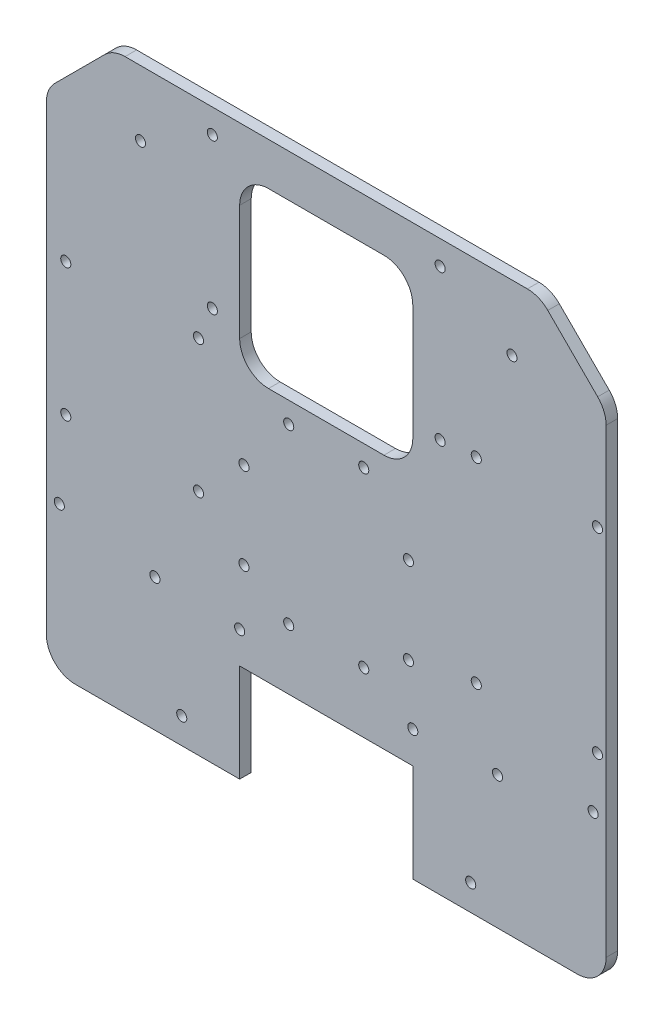
SolidWorks part; units mm, degrees
material "PMMA"
ref_plane "前视基准面" through (0, 0, 0) normal (0, 0, 1) x (1, 0, 0)
ref_plane "上视基准面" through (0, 0, 0) normal (0, 1, 0) x (1, 0, 0)
ref_plane "右视基准面" through (0, 0, 0) normal (1, 0, 0) x (0, 0, -1)
sketch "草图3" plane through (0, 0, 0) normal (0, 0, 1) x (1, 0, 0)
  line L1 (73.5057, 259.0895) -> (196.9372, 259.0895)
  line L2 (25.2215, 210.8052) -> (25.2215, 54.0895)
  line L3 (45.2215, 34.0895) -> (225.2215, 34.0895)
  line L4 (245.2215, 210.8052) -> (245.2215, 54.0895)
  line L6 (31.0793, 224.9474) -> (59.3636, 253.2316)
  line L9 (211.0793, 253.2316) -> (239.3636, 224.9474)
  arc A0 (73.5057, 259.0895) -> (59.3636, 253.2316) centre (73.5057, 239.0895) ccw
  arc A1 (211.0793, 253.2316) -> (196.9372, 259.0895) centre (196.9372, 239.0895) ccw
  arc A2 (31.0793, 224.9474) -> (25.2215, 210.8052) centre (45.2215, 210.8052) ccw
  arc A3 (25.2215, 54.0895) -> (45.2215, 34.0895) centre (45.2215, 54.0895) ccw
  arc A4 (225.2215, 34.0895) -> (245.2215, 54.0895) centre (225.2215, 54.0895) ccw
  arc A5 (245.2215, 210.8052) -> (239.3636, 224.9474) centre (225.2215, 210.8052) ccw
  dimension "D1" = 20
  dimension "D2" = 20
  dimension "D3" = 20
extrude "凸台-拉伸1" add sketch "草图3" along normal blind 4
ref_plane "基准面1" through (0, 0, 4) normal (0, 0, 1) x (1, 0, 0)
sketch "草图4" plane through (0, 0, 4) normal (0, 0, 1) x (1, 0, 0)
  line L0 (135.2215, 259.0895) -> (135.2215, 34.0895) construction
  line L1 (135.2215, 232.7454) -> (174.6915, 232.7454) construction
  line L2 (154.9565, 232.7454) -> (154.9565, 180.6354) construction
  line L4 (135.2215, 180.6354) -> (154.9565, 180.6354) construction
  line L6 (154.9565, 206.6904) -> (187.4334, 206.6904) construction
  line L10 (196.9372, 259.0895) -> (73.5057, 259.0895) construction
  line L11 (45.2215, 34.0895) -> (225.2215, 34.0895) construction
  line L13 (135.2215, 89.0683) -> (165.2215, 89.0683) construction
  circle A5 centre (174.6915, 232.7454) radius 1.75
  circle A14 centre (174.6915, 180.6354) radius 1.75
  circle A15 centre (95.7515, 180.6354) radius 1.75
  circle A16 centre (95.7515, 232.7454) radius 1.75
  circle A17 centre (165.2215, 89.0683) radius 1.75
  circle A18 centre (105.2215, 89.0683) radius 1.75
sketch "草图6" plane through (0, 0, 4) normal (0, 0, 1) x (1, 0, 0)
  line L0 (135.2215, 265.6507) -> (135.2215, 27.2875) construction
  line L1 (187.2215, 181.7201) -> (187.2215, 113.8801) construction
  line L4 (229.2215, 181.7201) -> (229.2215, 113.8801) construction
  line L6 (187.2215, 181.7201) -> (229.2215, 181.7201) construction
  line L7 (187.2215, 113.8801) -> (229.2215, 113.8801) construction
  circle A0 centre (187.2215, 181.7201) radius 1.75
  circle A1 centre (229.2215, 181.7201) radius 1.75
  circle A2 centre (229.2215, 113.8801) radius 1.75
  circle A3 centre (187.2215, 113.8801) radius 1.75
extrude "切除-拉伸3" cut sketch "草图6" against normal blind 4
extrude "切除-拉伸4" cut sketch "草图4" against normal blind 4
sketch "草图7" plane through (0, 0, 4) normal (0, 0, 1) x (1, 0, 0)
  circle A0 centre (122.2215, 159.0895) radius 1.75
  circle A1 centre (148.2215, 159.0895) radius 1.75
  circle A2 centre (122.2215, 99.0895) radius 1.75
  circle A3 centre (148.2215, 99.0895) radius 1.75
extrude "切除-拉伸5" cut sketch "草图7" against normal blind 4
sketch "草图8" plane through (0, 0, 4) normal (0, 0, 1) x (1, 0, 0)
  line L0 (25.2215, 132.4474) -> (245.2215, 132.4474) construction
  line L1 (105.2215, 89.0683) -> (165.2215, 89.0683) construction
  line L2 (227.7201, 95.4947) -> (185.2937, 53.0683) construction
  line L4 (25.2215, 210.8052) -> (25.2215, 54.0895) construction
  line L5 (245.2215, 210.8052) -> (245.2215, 54.0895) construction
  line L7 (135.2215, 259.0895) -> (135.2215, 34.0895) construction
  circle A2 centre (227.7201, 95.4947) radius 1.75
  circle A3 centre (185.2937, 53.0683) radius 1.75
  circle A4 centre (42.7229, 95.4947) radius 1.75
  circle A5 centre (85.1493, 53.0683) radius 1.75
extrude "切除-拉伸6" cut sketch "草图8" against normal blind 4
sketch "草图9" plane through (0, 0, 4) normal (0, 0, 1) x (1, 0, 0)
  line L0 (115.2215, 166.3247) -> (155.2215, 166.3247)
  line L2 (135.2215, 226.3247) -> (115.2215, 226.3247)
  line L6 (155.2215, 226.3247) -> (135.2215, 226.3247)
  line L9 (105.2215, 196.1043) -> (105.2215, 176.3247)
  line L10 (105.2215, 166.3247) -> (115.2215, 166.3247)
  line L11 (115.2215, 226.3247) -> (105.2215, 226.3247)
  line L12 (105.2215, 216.3247) -> (105.2215, 196.1043)
  line L13 (155.2215, 226.3247) -> (165.2215, 226.3247)
  line L14 (165.2215, 216.3247) -> (165.2215, 176.3247)
  line L15 (165.2215, 166.3247) -> (155.2215, 166.3247)
  arc A0 (165.2215, 216.3247) -> (155.2215, 226.3247) centre (155.2215, 216.3247) ccw
  arc A1 (165.2215, 176.3247) -> (155.2215, 166.3247) centre (155.2215, 176.3247) cw
  arc A2 (115.2215, 166.3247) -> (105.2215, 176.3247) centre (115.2215, 176.3247) cw
  arc A3 (105.2215, 216.3247) -> (115.2215, 226.3247) centre (115.2215, 216.3247) cw
  dimension "D1" = 10
extrude "切除-拉伸7" cut sketch "草图9" against normal blind 4
sketch "草图10" plane through (0, 0, 4) normal (0, 0, 1) x (1, 0, 0)
  line L0 (135.2215, 259.0895) -> (135.2215, 34.0895) construction
  line L1 (196.9372, 259.0895) -> (73.5057, 259.0895) construction
  line L2 (45.2215, 34.0895) -> (225.2215, 34.0895) construction
  line L3 (106.7215, 109.0895) -> (106.7215, 139.0895) construction
  line L4 (106.7215, 139.0895) -> (163.7215, 139.0895) construction
  line L5 (163.7215, 139.0895) -> (163.7215, 109.0895) construction
  line L6 (163.7215, 109.0895) -> (106.7215, 109.0895) construction
  line L7 (45.2215, 34.0895) -> (225.2215, 34.0895) construction
  circle A2 centre (106.7215, 109.0895) radius 1.75
  circle A3 centre (163.7215, 109.0895) radius 1.75
  circle A4 centre (106.7215, 139.0895) radius 1.75
  circle A5 centre (163.7215, 139.0895) radius 1.75
  dimension "D1" = 75
extrude "切除-拉伸9" cut sketch "草图10" against normal blind 4
sketch "草图11" plane through (0, 0, 4) normal (0, 0, 1) x (1, 0, 0)
  line L0 (26.7439, 218.4589) -> (243.6991, 218.4589) construction
  line L1 (65.8521, 257.5671) -> (65.8521, 34.0895) construction
  line L2 (45.2215, 34.0895) -> (225.2215, 34.0895) construction
  line L3 (204.5909, 131.2717) -> (65.8521, 131.2717) construction
  line L4 (25.2215, 54.0895) -> (245.2215, 54.0895) construction
  line L5 (135.2215, 259.0895) -> (135.2215, 34.0895) construction
  line L10 (73.254, 90.0846) -> (74.553, 87.8346)
  line L11 (73.4502, 218.4589) -> (72.1511, 220.7089)
  line L12 (196.9372, 259.0895) -> (73.5057, 259.0895) construction
  line L13 (204.5909, 218.4589) -> (204.5909, 44.0846) construction
  line L26 (75.8521, 90.0846) -> (75.8521, 218.4589) construction
  line L27 (72.1511, 220.7089) -> (69.553, 220.7089)
  line L28 (69.553, 220.7089) -> (68.254, 218.4589)
  line L29 (68.254, 218.4589) -> (69.553, 216.2089)
  line L30 (69.553, 216.2089) -> (72.1511, 216.2089)
  line L31 (72.1511, 216.2089) -> (73.4502, 218.4589)
  line L32 (77.1511, 87.8346) -> (78.4502, 90.0846)
  line L33 (74.553, 87.8346) -> (77.1511, 87.8346)
  line L34 (78.4502, 90.0846) -> (77.1511, 92.3346)
  line L35 (74.553, 92.3346) -> (73.254, 90.0846)
  line L36 (77.1511, 92.3346) -> (74.553, 92.3346)
  line L37 (191.9928, 90.0846) -> (193.2918, 87.8346)
  line L38 (195.8899, 87.8346) -> (197.1889, 90.0846)
  line L39 (193.2918, 87.8346) -> (195.8899, 87.8346)
  line L40 (197.1889, 90.0846) -> (195.8899, 92.3346)
  line L41 (193.2918, 92.3346) -> (191.9928, 90.0846)
  line L42 (195.8899, 92.3346) -> (193.2918, 92.3346)
  line L43 (196.9928, 218.4589) -> (198.2918, 216.2089)
  line L44 (200.8899, 216.2089) -> (202.1889, 218.4589)
  line L45 (198.2918, 216.2089) -> (200.8899, 216.2089)
  line L46 (202.1889, 218.4589) -> (200.8899, 220.7089)
  line L47 (198.2918, 220.7089) -> (196.9928, 218.4589)
  line L48 (200.8899, 220.7089) -> (198.2918, 220.7089)
  arc A0 (31.0793, 224.9474) -> (25.2215, 210.8052) centre (45.2215, 210.8052) ccw construction
  arc A1 (245.2215, 210.8052) -> (239.3636, 224.9474) centre (225.2215, 210.8052) ccw construction
  arc A2 (73.5057, 259.0895) -> (59.3636, 253.2316) centre (73.5057, 239.0895) ccw construction
  circle A3 centre (70.8521, 218.4589) radius 1.75
  circle A12 centre (75.8521, 90.0846) radius 1.75
  circle A13 centre (194.5909, 90.0846) radius 1.75
  circle A15 centre (199.5909, 218.4589) radius 1.75
  circle A16 centre (70.8521, 218.4589) radius 2.25 construction
  point P26 (65.8521, 218.4589)
  dimension "D1" = 4.5
extrude "切除-拉伸10" cut sketch "草图11" against normal up to next
ref_plane "基准面2" through (0, 0, 4) normal (0, 0, 1) x (1, 0, 0)
sketch "草图12" plane through (0, 0, 4) normal (0, 0, 1) x (1, 0, 0)
  line L0 (41.9614, 172.3122) -> (41.9614, 165.6511) construction
  line L1 (41.9614, 172.3122) -> (93.9614, 172.3122)
  line L2 (41.9614, 172.3122) -> (41.9614, 120.3122)
  line L3 (41.9614, 120.3122) -> (93.9614, 120.3122)
  line L4 (93.9614, 172.3122) -> (93.9614, 120.3122)
  line L5 (41.9614, 172.3122) -> (93.9614, 120.3122) construction
  line L6 (41.9614, 120.3122) -> (93.9614, 172.3122) construction
  line L7 (41.9614, 172.3122) -> (41.9614, 166.5784) construction
  line L8 (41.9614, 166.5784) -> (41.9614, 164.5784) construction
  line L9 (93.9614, 172.3122) -> (93.9614, 169.3122) construction
  line L10 (93.9614, 169.3122) -> (90.9614, 169.3122) construction
  circle A0 centre (90.9614, 169.3122) radius 1.75
  circle A1 centre (90.9614, 123.3122) radius 1.75
  circle A2 centre (44.9614, 123.3122) radius 1.75
  circle A3 centre (44.9614, 169.3122) radius 1.75
  point P0 (67.9614, 146.3122)
  point P20 (67.9614, 146.3122)
  dimension "D1" = 4
extrude "切除-拉伸13" cut sketch "草图12" against normal through all contours A3 | A2 | A1 | A0
sketch "草图13" plane through (0, 0, 4) normal (0, 0, 1) x (1, 0, 0)
  line L0 (45.2215, 34.0895) -> (225.2215, 34.0895) construction
  line L1 (105.2215, 68.0683) -> (165.2215, 68.0683)
  line L2 (105.2215, 68.0683) -> (105.2215, 34.0895)
  line L3 (105.2215, 34.0895) -> (165.2215, 34.0895)
  line L4 (165.2215, 68.0683) -> (165.2215, 34.0895)
  line L5 (165.2215, 54.0895) -> (105.2215, 54.0895)
  line L6 (25.2215, 54.0895) -> (245.2215, 54.0895) construction
extrude "切除-拉伸14" cut sketch "草图13" against normal blind 10 contours L4 L5 L2 L3
sketch "草图14" plane through (0, 0, 0) normal (0, 0, 1) x (1, 0, 0)
  line L0 (105.2215, 68.0683) -> (165.2215, 68.0683)
  line L10 (105.2215, 68.0683) -> (165.2215, 68.0683)
  line L11 (165.2215, 68.0683) -> (165.2215, 34.0895)
  line L12 (165.2215, 34.0895) -> (225.2215, 34.0895)
  line L13 (245.2215, 54.0895) -> (245.2215, 210.8052)
  line L14 (239.3636, 224.9474) -> (211.0793, 253.2316)
  line L15 (196.9372, 259.0895) -> (73.5057, 259.0895)
  line L16 (59.3636, 253.2316) -> (31.0793, 224.9474)
  line L17 (25.2215, 210.8052) -> (25.2215, 54.0895)
  line L18 (45.2215, 34.0895) -> (105.2215, 34.0895)
  line L19 (105.2215, 34.0895) -> (105.2215, 68.0683)
  line L21 (165.2215, 44.0895) -> (165.2215, 34.0895)
  line L22 (165.2215, 34.0895) -> (225.2215, 34.0895)
  line L23 (245.2215, 54.0895) -> (245.2215, 210.8052)
  line L24 (239.3636, 224.9474) -> (211.0793, 253.2316)
  line L25 (196.9372, 259.0895) -> (73.5057, 259.0895)
  line L26 (59.3636, 253.2316) -> (31.0793, 224.9474)
  line L27 (25.2215, 210.8052) -> (25.2215, 54.0895)
  line L28 (45.2215, 34.0895) -> (105.2215, 34.0895)
  line L29 (105.2215, 34.0895) -> (105.2215, 44.0895)
  line L30 (38.2215, 210.8052) -> (38.2215, 54.0895)
  line L31 (232.2215, 54.0895) -> (232.2215, 213.8052)
  line L32 (196.9372, 241.0895) -> (73.5057, 241.0895)
  line L33 (73.5057, 241.0895) -> (65.5057, 241.0895)
  line L34 (38.2215, 210.8052) -> (38.2215, 213.8052)
  line L35 (196.9372, 241.0895) -> (204.9372, 241.0895)
  line L36 (232.2215, 210.8052) -> (232.2215, 213.8052)
  line L40 (95.2215, 78.0683) -> (175.2215, 78.0683)
  line L41 (175.2215, 78.0683) -> (175.2215, 44.0895)
  line L42 (175.2215, 44.0895) -> (225.2215, 44.0895)
  line L43 (235.2215, 54.0895) -> (235.2215, 210.8052)
  line L44 (232.2925, 217.8763) -> (204.0083, 246.1606)
  line L45 (196.9372, 249.0895) -> (73.5057, 249.0895)
  line L46 (66.4347, 246.1606) -> (38.1504, 217.8763)
  line L47 (35.2215, 210.8052) -> (35.2215, 54.0895)
  line L48 (45.2215, 44.0895) -> (95.2215, 44.0895)
  line L49 (95.2215, 44.0895) -> (95.2215, 78.0683)
  line L50 (105.2215, 78.0683) -> (165.2215, 78.0683)
  line L52 (175.2215, 44.0895) -> (222.2215, 44.0895)
  line L54 (229.2925, 220.8763) -> (212.0083, 238.1606)
  line L56 (58.4347, 238.1606) -> (41.1504, 220.8763)
  line L58 (48.2215, 44.0895) -> (95.2215, 44.0895)
  line L61 (105.2215, 78.0683) -> (105.2215, 68.0683)
  line L62 (95.2215, 44.0895) -> (105.2215, 44.0895)
  line L63 (165.2215, 78.0683) -> (165.2215, 68.0683)
  line L64 (175.2215, 44.0895) -> (165.2215, 44.0895)
  arc A6 (225.2215, 34.0895) -> (245.2215, 54.0895) centre (225.2215, 54.0895) ccw
  arc A7 (245.2215, 210.8052) -> (239.3636, 224.9474) centre (225.2215, 210.8052) ccw
  arc A8 (211.0793, 253.2316) -> (196.9372, 259.0895) centre (196.9372, 239.0895) ccw
  arc A9 (73.5057, 259.0895) -> (59.3636, 253.2316) centre (73.5057, 239.0895) ccw
  arc A10 (31.0793, 224.9474) -> (25.2215, 210.8052) centre (45.2215, 210.8052) ccw
  arc A11 (25.2215, 54.0895) -> (45.2215, 34.0895) centre (45.2215, 54.0895) ccw
  arc A12 (225.2215, 34.0895) -> (245.2215, 54.0895) centre (225.2215, 54.0895) ccw
  arc A13 (245.2215, 210.8052) -> (239.3636, 224.9474) centre (225.2215, 210.8052) ccw
  arc A14 (211.0793, 253.2316) -> (196.9372, 259.0895) centre (196.9372, 239.0895) ccw
  arc A15 (73.5057, 259.0895) -> (59.3636, 253.2316) centre (73.5057, 239.0895) ccw
  arc A16 (31.0793, 224.9474) -> (25.2215, 210.8052) centre (45.2215, 210.8052) ccw
  arc A17 (25.2215, 54.0895) -> (45.2215, 34.0895) centre (45.2215, 54.0895) ccw
  arc A18 (222.2215, 44.0895) -> (232.2215, 54.0895) centre (222.2215, 54.0895) ccw
  arc A19 (48.2215, 44.0895) -> (38.2215, 54.0895) centre (48.2215, 54.0895) cw
  arc A20 (212.0083, 238.1606) -> (204.9372, 241.0895) centre (204.9372, 231.0895) ccw
  arc A21 (58.4347, 238.1606) -> (65.5057, 241.0895) centre (65.5057, 231.0895) cw
  arc A22 (232.2215, 213.8052) -> (229.2925, 220.8763) centre (222.2215, 213.8052) ccw
  arc A23 (38.2215, 213.8052) -> (41.1504, 220.8763) centre (48.2215, 213.8052) cw
  arc A24 (225.2215, 44.0895) -> (235.2215, 54.0895) centre (225.2215, 54.0895) ccw
  arc A25 (235.2215, 210.8052) -> (232.2925, 217.8763) centre (225.2215, 210.8052) ccw
  arc A26 (204.0083, 246.1606) -> (196.9372, 249.0895) centre (196.9372, 239.0895) ccw
  arc A27 (73.5057, 249.0895) -> (66.4347, 246.1606) centre (73.5057, 239.0895) ccw
  arc A28 (38.1504, 217.8763) -> (35.2215, 210.8052) centre (45.2215, 210.8052) ccw
  arc A29 (35.2215, 54.0895) -> (45.2215, 44.0895) centre (45.2215, 54.0895) ccw
  dimension "D3" = 10
  dimension "D4" = 10
  dimension "D1" = 0
  dimension "D2" = 10
extrude "切除-拉伸16" cut sketch "草图14" along normal blind 10 contours L34 A23 L56 A21 L33 L32 L35 A20 L54 A22 L31 A18 L52 L64 L21 L22 A12 L23 A13 L24 A14 L25 A15 L26 A16 L27 A17 L28 L29 L62 L58 A19 L30 | L63 L50 L61 L0
